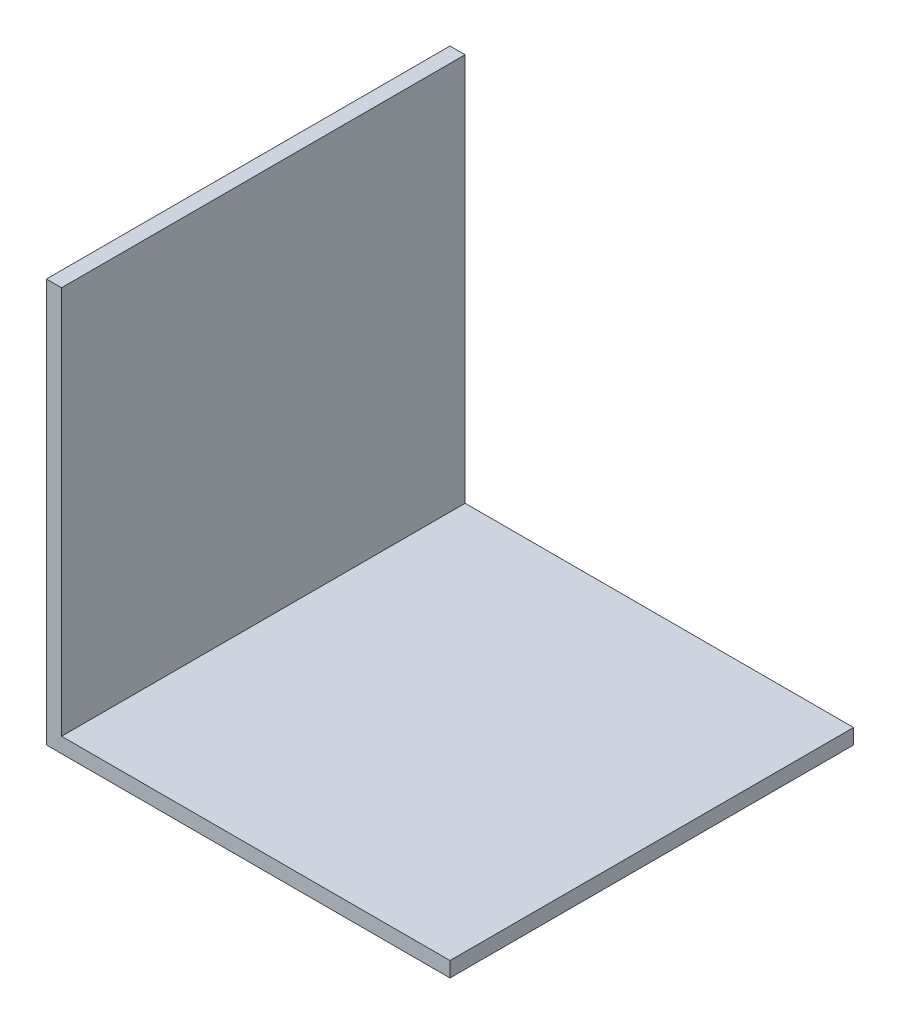
SolidWorks part; units mm, degrees
material "Листовая углеродистая сталь 1023 (SS)"
ref_plane "Спереди" through (0, 0, 0) normal (0, 0, 1) x (1, 0, 0)
ref_plane "Сверху" through (0, 0, 0) normal (0, 1, 0) x (1, 0, 0)
ref_plane "Справа" through (0, 0, 0) normal (1, 0, 0) x (0, 0, -1)
sketch "Эскиз1" plane through (0, 0, 0) normal (0, 0, 1) x (1, 0, 0)
  line L0 (0, 0) -> (40, 0)
  line L1 (40, 0) -> (40, 1.5)
  line L2 (40, 1.5) -> (1.5, 1.5)
  line L3 (1.5, 1.5) -> (1.5, 40)
  line L4 (1.5, 40) -> (0, 40)
  line L5 (0, 40) -> (0, 0)
  dimension "D1" = 1.5
  dimension "D2" = 1.5
  dimension "D3" = 40
  dimension "D4" = 40
extrude "Бобышка-Вытянуть1" add sketch "Эскиз1" along normal blind 40
